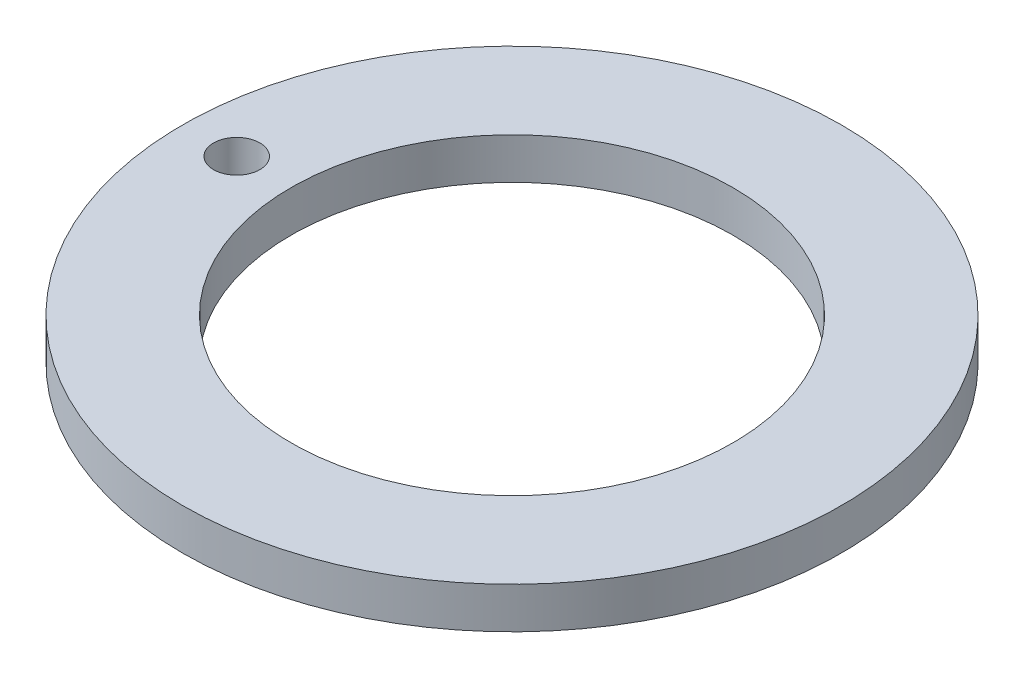
SolidWorks part; units mm, degrees
material "6061 Alloy"
ref_plane "Front Plane" through (0, 0, 0) normal (0, 0, 1) x (1, 0, 0)
ref_plane "Top Plane" through (0, 0, 0) normal (0, 1, 0) x (1, 0, 0)
ref_plane "Right Plane" through (0, 0, 0) normal (1, 0, 0) x (0, 0, -1)
sketch "Sketch1" plane through (0, 0, 0) normal (0, 1, 0) x (1, 0, 0)
  circle A0 centre (0, 0) radius 51.1048
  circle A1 centre (0, 0) radius 76.2
  dimension "D1" = 102.2096
  dimension "D2" = 152.4
extrude "Boss-Extrude1" add sketch "Sketch1" along normal blind 9.525
sketch "Sketch2" plane through (0, 9.525, 0) normal (0, 1, 0) x (1, 0, 0)
  line L0 (-51.1048, 0) -> (-76.2, 0) construction
  circle A0 centre (0, 0) radius 51.1048 construction
  circle A1 centre (0, 0) radius 76.2 construction
  circle A2 centre (-63.6524, 0) radius 5.3581
  dimension "D1" = 10.7163
extrude "Cut-Extrude1" cut sketch "Sketch2" against normal through all
equation "\"Ring Thickness\"= 0.375"
equation "\"Outer Diameter\"= 6"
equation "\"Inner Diameter\"= 4.024"
equation "\"D1@Sketch1\"=\"Inner Diameter\""
equation "\"D2@Sketch1\"=\"Outer Diameter\""
equation "\"D1@Boss-Extrude1\"=\"Ring Thickness\""
